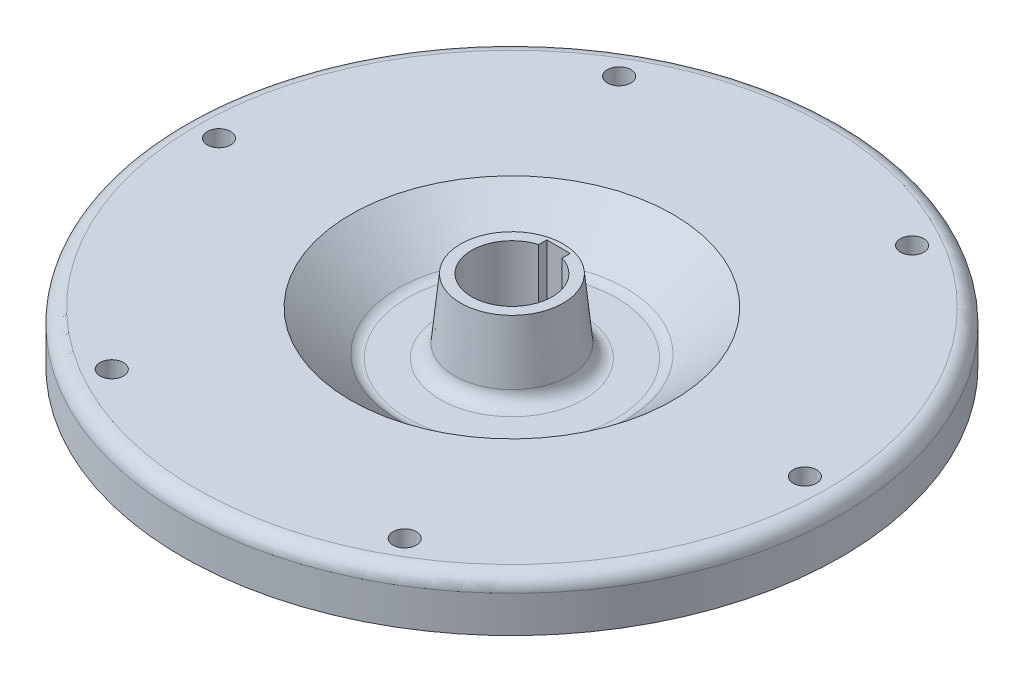
SolidWorks part; units mm, degrees
material "1060 Alloy"
ref_plane "Front Plane" through (0, 0, 0) normal (0, 0, 1) x (1, 0, 0)
ref_plane "Top Plane" through (0, 0, 0) normal (0, 1, 0) x (1, 0, 0)
ref_plane "Right Plane" through (0, 0, 0) normal (1, 0, 0) x (0, 0, -1)
sketch "Sketch1" plane through (0, 0, 0) normal (0, 0, 1) x (1, 0, 0)
  line L0 (0, 0) -> (0, 200) construction
  line L1 (27.5, 0) -> (65, 0)
  line L2 (75, 10) -> (75, 35)
  line L3 (110, 70) -> (175, 70)
  line L4 (175, 70) -> (175, 105)
  line L5 (175, 105) -> (225, 105)
  line L6 (225, 105) -> (225, 130)
  line L7 (215, 140) -> (110, 140)
  line L8 (110, 140) -> (77.8087, 112.4074)
  line L9 (71.3008, 110) -> (49.0499, 110)
  line L10 (39.0995, 119.005) -> (35, 160)
  line L11 (35, 160) -> (27.5, 160)
  line L12 (27.5, 0) -> (27.5, 160)
  arc A0 (75, 35) -> (110, 70) centre (110, 35) cw
  arc A1 (65, 0) -> (75, 10) centre (65, 10) ccw
  arc A2 (49.0499, 110) -> (39.0995, 119.005) centre (49.0499, 120) cw
  arc A3 (77.8087, 112.4074) -> (71.3008, 110) centre (71.3008, 120) cw
  arc A4 (225, 130) -> (215, 140) centre (215, 130) ccw
  point P31 (40, 110)
  point P34 (75, 110)
  dimension "D1" = 55
  dimension "D8" = 35
  dimension "D13" = 10
  dimension "D2" = 150
  dimension "D3" = 350
  dimension "D4" = 160
  dimension "D5" = 35
  dimension "D6" = 450
  dimension "D7" = 20
  dimension "D9" = 35
  dimension "D10" = 30
  dimension "D11" = 70
  dimension "D12" = 5
revolve "Revolve1" add sketch "Sketch1" angle 360 about L0
sketch "Sketch2" plane through (0, 140, 0) normal (0, 1, 0) x (1, 0, 0)
  circle A0 centre (0, 0) radius 200 construction
  circle A1 centre (200, 0) radius 8
  circle A2 centre (100, -173.2051) radius 8
  circle A3 centre (-100, -173.2051) radius 8
  circle A4 centre (-200, 0) radius 8
  circle A5 centre (-100, 173.2051) radius 8
  circle A6 centre (100, 173.2051) radius 8
  point P18 (0, 0)
  dimension "D1" = 400
  dimension "D2" = 16
  dimension "D3" = 6
extrude "Cut-Extrude1" cut sketch "Sketch2" against normal through all both
sketch "Sketch3" plane through (0, 160, 0) normal (0, 1, 0) x (1, 0, 0)
  line L0 (-8, 26.3106) -> (-8, 31.8)
  line L1 (-8, 31.8) -> (8, 31.8)
  line L2 (8, 31.8) -> (8, 26.3106)
  circle A0 centre (0, 0) radius 27.5 construction
  arc A1 (8, 26.3106) -> (-8, 26.3106) centre (0, 0) ccw
  point P7 (0, 31.8)
  point P9 (0, 27.5)
  dimension "D1" = 4.3
  dimension "D2" = 16
extrude "Cut-Extrude2" cut sketch "Sketch3" against normal through all both
